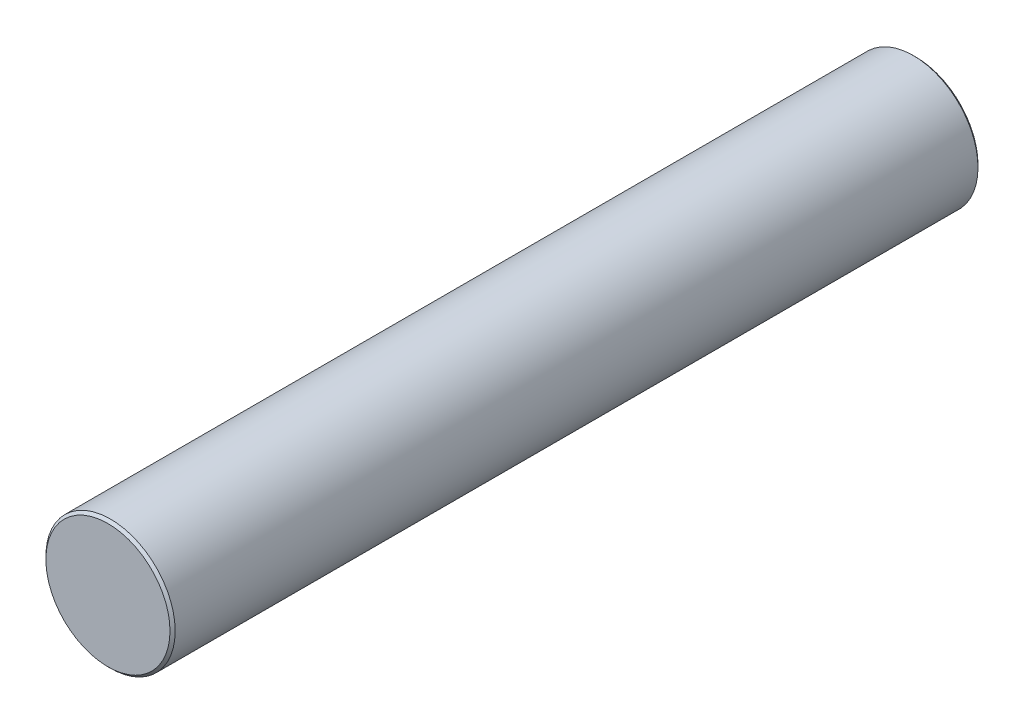
SolidWorks part; units mm, degrees
ref_plane "Front Plane" through (0, 0, 0) normal (0, 0, 1) x (1, 0, 0)
ref_plane "Top Plane" through (0, 0, 0) normal (0, 1, 0) x (1, 0, 0)
ref_plane "Right Plane" through (0, 0, 0) normal (1, 0, 0) x (0, 0, -1)
sketch "Sketch1" plane through (0, 0, 0) normal (1, 0, 0) x (0, 0, -1)
  line L0 (-25, 0) -> (25, 0) construction
  line L1 (0, -4) -> (0, 4) construction
  point P4 (0, 0)
  point P8 (0, 0)
sketch "Sketch2" plane through (0, 0, 0) normal (0, 0, 1) x (1, 0, 0)
  circle A0 centre (0, 0) radius 4
extrude "Boss-Extrude1" add sketch "Sketch2" along normal up to vertex (25 mm away) and the other way up to vertex (25 mm away) up to point (0, 0, 25) other way up to point (0, 0, -25)
chamfer "Chamfer1" distance 0.16 angle 45 2 edges at (4, 0, -25) (4, 0, 25)
equation "\"D1@Chamfer1\"=\"Diameter@Sketch1\"*.02"
